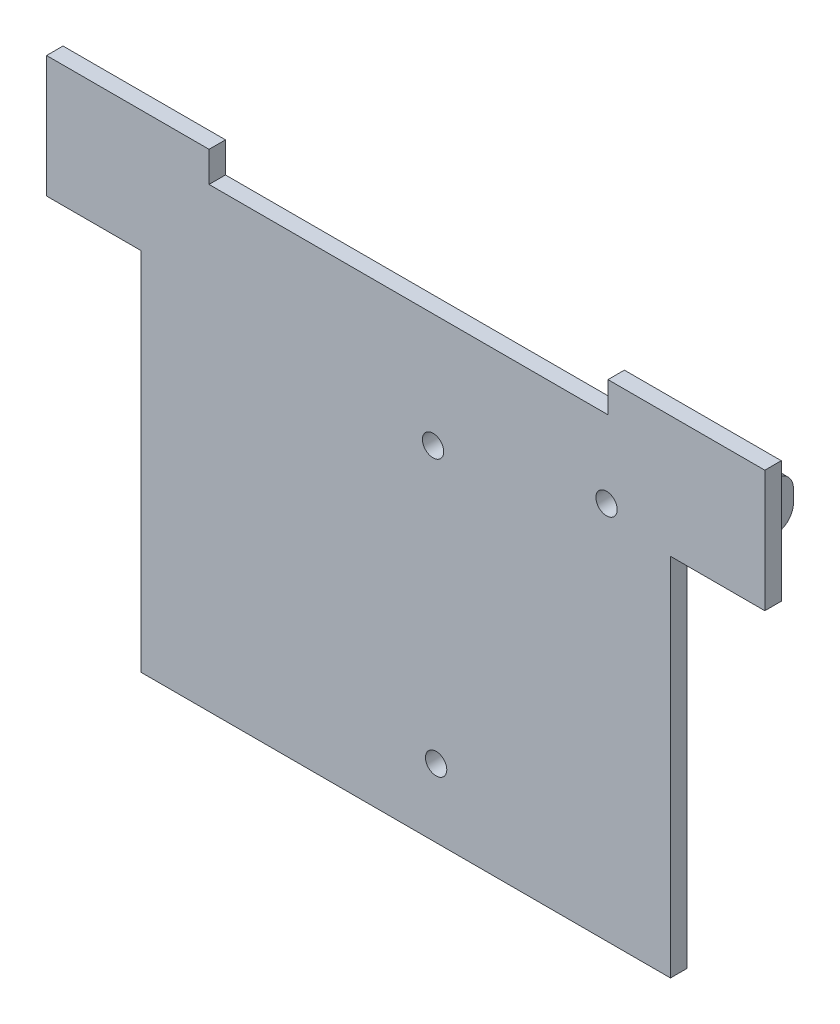
SolidWorks part; units mm, degrees
ref_plane "Front Plane" through (0, 0, 0) normal (0, 0, 1) x (1, 0, 0)
ref_plane "Top Plane" through (0, 0, 0) normal (0, 1, 0) x (1, 0, 0)
ref_plane "Right Plane" through (0, 0, 0) normal (1, 0, 0) x (0, 0, -1)
sketch "Sketch1" plane through (0, 0, 0) normal (0, 0, 1) x (1, 0, 0)
  line L1 (-73.7662, 56) -> (44.2338, 56)
  line L2 (-73.7662, 56) -> (-73.7662, -24)
  line L3 (-73.7662, -24) -> (44.2338, -24)
  line L4 (44.2338, 56) -> (44.2338, -24)
  dimension "D1" = 118
  dimension "D2" = 80
extrude "Boss-Extrude1" add sketch "Sketch1" along normal blind 2.7
sketch "Sketch3" plane through (0, 0, 2.7) normal (0, 0, 1) x (1, 0, 0)
  line L0 (44.2338, 56) -> (-73.7662, 56) construction
  line L1 (-73.7662, -24) -> (-68.2662, -24)
  line L2 (-73.7662, -24) -> (-73.7662, 36)
  line L3 (-73.7662, 36) -> (-68.2662, 36)
  line L4 (-68.2662, -24) -> (-68.2662, 36)
  line L5 (44.2338, -24) -> (38.7338, -24)
  line L6 (44.2338, -24) -> (44.2338, 36)
  line L7 (44.2338, 36) -> (38.7338, 36)
  line L8 (38.7338, -24) -> (38.7338, 36)
  dimension "D1" = 5.5
  dimension "D2" = 5.5
  dimension "D3" = 60
  dimension "D4" = 60
  dimension "D5" = 20
extrude "Cut-Extrude1" cut sketch "Sketch3" against normal blind 2.7
sketch "Sketch4" plane through (0, 0, 2.7) normal (0, 0, 1) x (1, 0, 0)
  line L0 (-68.2662, -24) -> (38.7338, -24) construction
  line L1 (-68.2662, 36) -> (-58.2662, 36)
  line L2 (-68.2662, 36) -> (-68.2662, -24)
  line L3 (-68.2662, -24) -> (-58.2662, -24)
  line L4 (-58.2662, 36) -> (-58.2662, -24)
  line L6 (38.7338, 36) -> (28.7338, 36)
  line L7 (38.7338, 36) -> (38.7338, -24)
  line L8 (38.7338, -24) -> (28.7338, -24)
  line L9 (28.7338, 36) -> (28.7338, -24)
  dimension "D1" = 10
  dimension "D2" = 10
extrude "Cut-Extrude2" cut sketch "Sketch4" against normal blind 2.7
sketch "Sketch7" plane through (0, 0, 0) normal (0, 0, -1) x (-1, 0, 0)
  line L0 (58.2662, 36) -> (73.7662, 36) construction
  line L1 (67.7662, 40) -> (63.7662, 40)
  line L2 (67.7662, 40) -> (67.7662, 48)
  line L3 (67.7662, 48) -> (63.7662, 48)
  line L4 (63.7662, 40) -> (63.7662, 48)
  line L5 (-38.2338, 40) -> (-34.2338, 40)
  line L6 (-38.2338, 40) -> (-38.2338, 48)
  line L7 (-38.2338, 48) -> (-34.2338, 48)
  line L8 (-34.2338, 40) -> (-34.2338, 48)
  line L9 (-44.2338, 36) -> (-28.7338, 36) construction
  line L10 (-44.2338, 36) -> (-44.2338, 56) construction
  line L11 (73.7662, 56) -> (73.7662, 36) construction
  dimension "D1" = 4
  dimension "D2" = 8
  dimension "D3" = 4
  dimension "D4" = 8
  dimension "D5" = 4
  dimension "D6" = 4
  dimension "D7" = 6
  dimension "D8" = 6
extrude "Boss-Extrude5" add sketch "Sketch7" along normal blind 8
sketch "Sketch8" plane through (38.2338, 0, 0) normal (1, 0, 0) x (0, 0, -1)
  line L0 (8, 40) -> (0, 40) construction
  line L1 (8, 48) -> (8, 40) construction
  circle A0 centre (4, 44) radius 1.75
  dimension "D1" = 3.5
  dimension "D2" = 4
  dimension "D3" = 4
extrude "Cut-Extrude4" cut sketch "Sketch8" against normal blind 131
fillet "Fillet1" radius 3 8 edges at (36.2338, 48, 0) (36.2338, 48, -8) (36.2338, 40, -8) (36.2338, 40, 0) (-65.7662, 40, -8) (-65.7662, 48, -8) (-65.7662, 48, 0) (-65.7662, 40, 0)
sketch "Sketch9" plane through (0, 0, 2.7) normal (0, 0, 1) x (1, 0, 0)
  line L0 (44.2338, 56) -> (-73.7662, 56) construction
  line L1 (-47.073, 56) -> (18.4609, 56)
  line L2 (-47.073, 56) -> (-47.073, 51)
  line L3 (-47.073, 51) -> (18.4609, 51)
  line L4 (18.4609, 56) -> (18.4609, 51)
  dimension "D1" = 5
extrude "Cut-Extrude5" cut sketch "Sketch9" against normal blind 53
sketch "Sketch10" plane through (0, 0, 0) normal (0, 0, -1) x (-1, 0, 0)
  circle A0 centre (9.7662, -12.75) radius 1.75
  circle A1 centre (10.2662, 32.25) radius 1.75
  circle A2 centre (-18.2338, 38.25) radius 1.75
  dimension "D1" = 3.5
  dimension "D2" = 3.5
  dimension "D3" = 3.5
extrude "Cut-Extrude6" cut sketch "Sketch10" against normal blind 10
